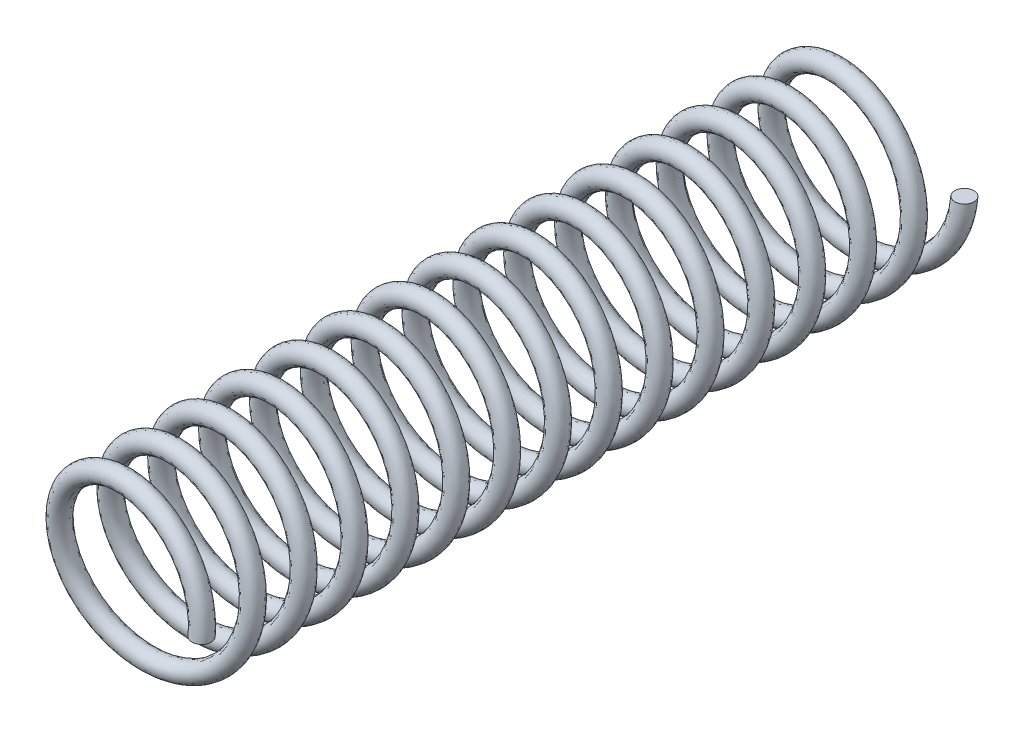
SolidWorks part; units mm, degrees
ref_plane "Front Plane" through (0, 0, 0) normal (0, 0, 1) x (1, 0, 0)
ref_plane "Top Plane" through (0, 0, 0) normal (0, 1, 0) x (1, 0, 0)
ref_plane "Right Plane" through (0, 0, 0) normal (1, 0, 0) x (0, 0, -1)
sketch "Sketch3" plane through (0, 0, 0) normal (0, 0, 1) x (1, 0, 0)
  circle A0 centre (0, 0) radius 3.56
curve "Helix/Spiral2" pitch 2.1667 height 32.5 turns 15
sketch "Sketch4" plane through (0, 0, 0) normal (0, 1, 0) x (1, 0, 0)
  circle A0 centre (3.56, 0) radius 0.41
sweep "Sweep1" add profiles "Sketch4" path "Helix/Spiral2"
